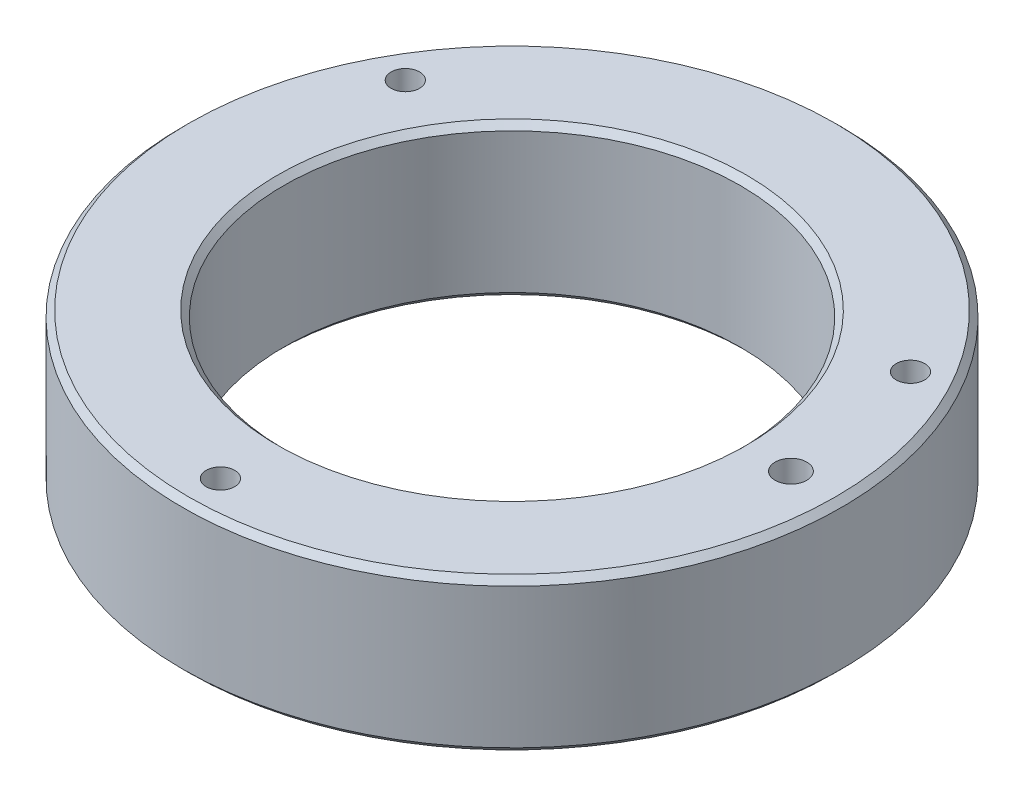
SolidWorks part; units mm, degrees
ref_plane "Front Plane" through (0, 0, 0) normal (1, 0, 0) x (0, 1, 0)
ref_plane "Top Plane" through (0, 0, 0) normal (0, 0, 1) x (0, 1, 0)
ref_plane "Right Plane" through (0, 0, 0) normal (0, 1, 0) x (-1, 0, 0)
sketch "Sketch1" plane through (0, 0, 0) normal (0, 0, 1) x (0, 1, 0)
  line L0 (-19.05, 82.5246) -> (19.05, 82.5246)
  line L1 (19.05, 82.5246) -> (19.05, 57.15)
  line L2 (19.05, 57.15) -> (-19.05, 57.15)
  line L3 (-19.05, 57.15) -> (-19.05, 82.5246)
  line L4 (-44.45, 0) -> (44.45, 0) construction
revolve "Revolve1" add sketch "Sketch1" angle 360 about L4
chamfer "Chamfer1" distance 1.524 angle 45 4 edges at (0, 19.05, -57.15) (0, -19.05, -57.15) (0, 19.05, -82.5246) (0, -19.05, -82.5246)
hole_wizard "CBORE for 1/4 Socket Head Cap Screw1" positions "Sketch3" profile "Sketch2" counterbore size "1/4" standard "ANSI Inch"
sketch "Sketch3" plane through (0, -19.05, 0) normal (0, -1, 0) x (-1, 0, 0)
  point P0 (0, -73.025)
  point P1 (-63.246, 36.5252)
  point P3 (63.246, 36.5252)
sketch "Sketch2" plane through (0, -19.05, 73.025) normal (1, 0, 0) x (0, 0, -1)
  line L0 (0, 0) -> (0, 40.2443)
  line L1 (0, 40.2443) -> (3.5687, 38.1)
  line L2 (3.5687, 38.1) -> (3.5687, 9.652)
  line L3 (3.5687, 9.652) -> (5.5626, 9.652)
  line L4 (5.5626, 9.652) -> (5.5626, 0)
  line L5 (5.5626, 0) -> (0, 0)
  line L10 (0, 40.2443) -> (-3.5687, 38.1) construction
  line L11 (0, -6.35) -> (0, 107.95) construction
  dimension "Hole Dia." = 7.1374
  dimension "Hole Depth" = 38.1
  dimension "C'Bore Dia." = 11.1252
  dimension "C'Bore Depth" = 9.652
  dimension "Drill Angle" = 118
hole_wizard "3/8-16 Tapped Hole1" positions "Sketch5" profile "Sketch4" tap size "3/8-16" standard "ANSI Inch"
sketch "Sketch5" plane through (0, -19.05, 0) normal (0, -1, 0) x (-1, 0, 0)
  point P0 (-69.85, 0)
sketch "Sketch4" plane through (69.85, -19.05, 0) normal (1, 0, 0) x (0, 0, -1)
  line L0 (0, 0) -> (0, 40.4847)
  line L1 (0, 40.4847) -> (3.9687, 38.1)
  line L2 (3.9687, 38.1) -> (3.9687, 0)
  line L5 (3.9687, 0) -> (0, 0)
  line L10 (0, 40.4847) -> (-3.9688, 38.1) construction
  line L11 (0, -6.35) -> (0, 107.95) construction
  dimension "Tap Drill Dia." = 7.9375
  dimension "Tap Drill Depth" = 38.1
  dimension "Drill Angle" = 118
cosmetic thread "Hole Thread1"
